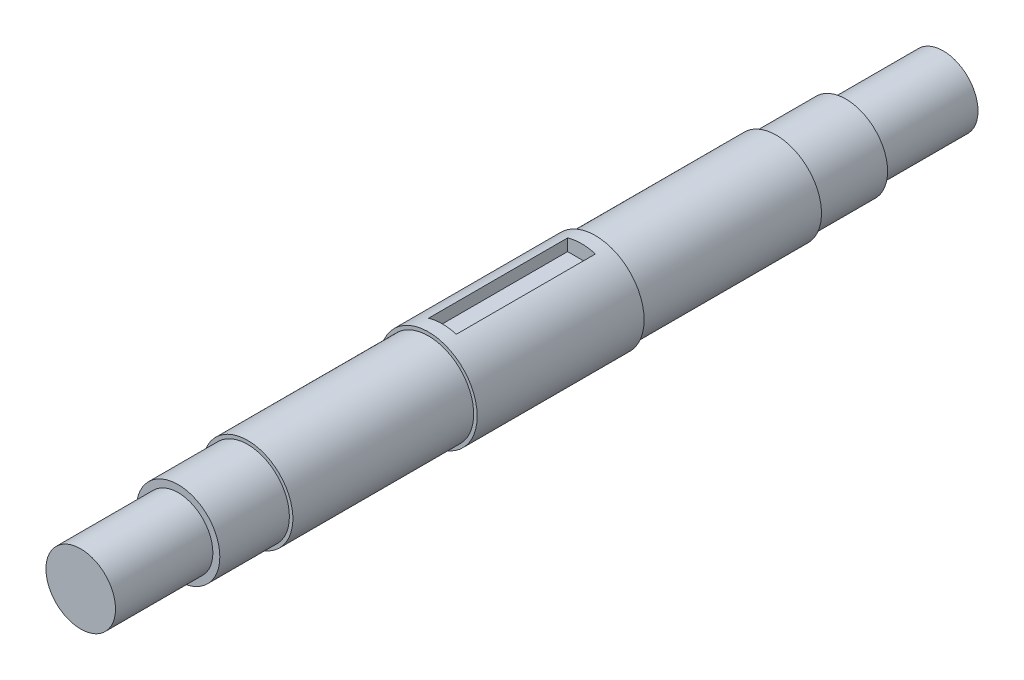
SolidWorks part; units mm, degrees
material "Plain Carbon Steel"
ref_plane "Front Plane" through (0, 0, 0) normal (1, 0, 0) x (0, 1, 0)
ref_plane "Top Plane" through (0, 0, 0) normal (0, 0, 1) x (0, 1, 0)
ref_plane "Right Plane" through (0, 0, 0) normal (0, 1, 0) x (-1, 0, 0)
sketch "Sketch1" plane through (0, 0, 0) normal (0, 0, 1) x (0, 1, 0)
  circle A0 centre (0, 0) radius 5
  dimension "D1" = 10
extrude "Boss-Extrude1" add sketch "Sketch1" along normal blind 14
sketch "Sketch2" plane through (0, 0, 14) normal (0, 0, 1) x (1, 0, 0)
  circle A0 centre (0, 0) radius 6
  dimension "D1" = 12
extrude "Boss-Extrude2" add sketch "Sketch2" along normal blind 10
sketch "Sketch3" plane through (0, 0, 24) normal (0, 0, 1) x (1, 0, 0)
  circle A0 centre (0, 0) radius 6.5
  dimension "D1" = 13
extrude "Boss-Extrude3" add sketch "Sketch3" along normal blind 26
sketch "Sketch4" plane through (0, 0, 50) normal (0, 0, 1) x (1, 0, 0)
  circle A0 centre (0, 0) radius 7
  dimension "D1" = 14
extrude "Boss-Extrude4" add sketch "Sketch4" along normal blind 12
ref_plane "Plane1" through (0, 0, 62) normal (0, 0, 1) x (0, -1, 0)
mirror "Mirror1" about plane through (0, 0, 62) normal (0, 0, 1) of bodies 104
ref_plane "Plane2" through (0, 7, 0) normal (0, 1, 0) x (-1, 0, 0)
sketch "Sketch5" plane through (0, 7, 0) normal (0, 1, 0) x (-1, 0, 0)
  line L0 (55, 62) -> (-55, 62) construction
  line L1 (-2, 72) -> (2, 72)
  line L2 (-2, 72) -> (-2, 52)
  line L3 (-2, 52) -> (2, 52)
  line L4 (2, 72) -> (2, 52)
  line L5 (-2, 72) -> (2, 52) construction
  line L6 (-2, 52) -> (2, 72) construction
  point P0 (0, 62)
  point P7 (0, 62)
  dimension "D1" = 2
  dimension "D2" = 20
  dimension "D3" = 4
extrude "Cut-Extrude2" cut sketch "Sketch5" against normal blind 2
